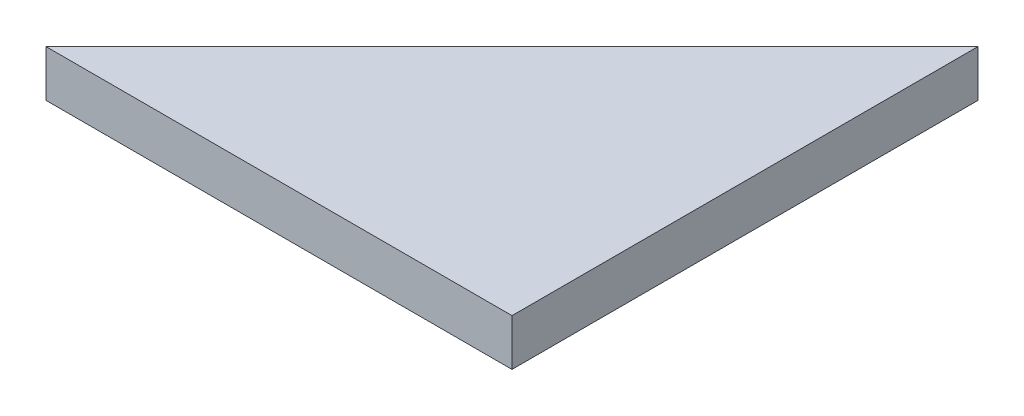
SolidWorks part; units mm, degrees
ref_plane "前视基准面" through (0, 0, 0) normal (0, 0, 1) x (1, 0, 0)
ref_plane "上视基准面" through (0, 0, 0) normal (0, 1, 0) x (1, 0, 0)
ref_plane "右视基准面" through (0, 0, 0) normal (1, 0, 0) x (0, 0, -1)
sketch "草图1" plane through (0, 0, 0) normal (0, 1, 0) x (1, 0, 0)
  line L0 (0, 0) -> (-30, 0)
  line L1 (-30, 0) -> (0, 30)
  line L2 (0, 30) -> (0, 0)
  point P4 (0, 36.7527)
  dimension "D1" = 45
  dimension "D2" = 30
extrude "凸台-拉伸1" add sketch "草图1" along normal blind 3
